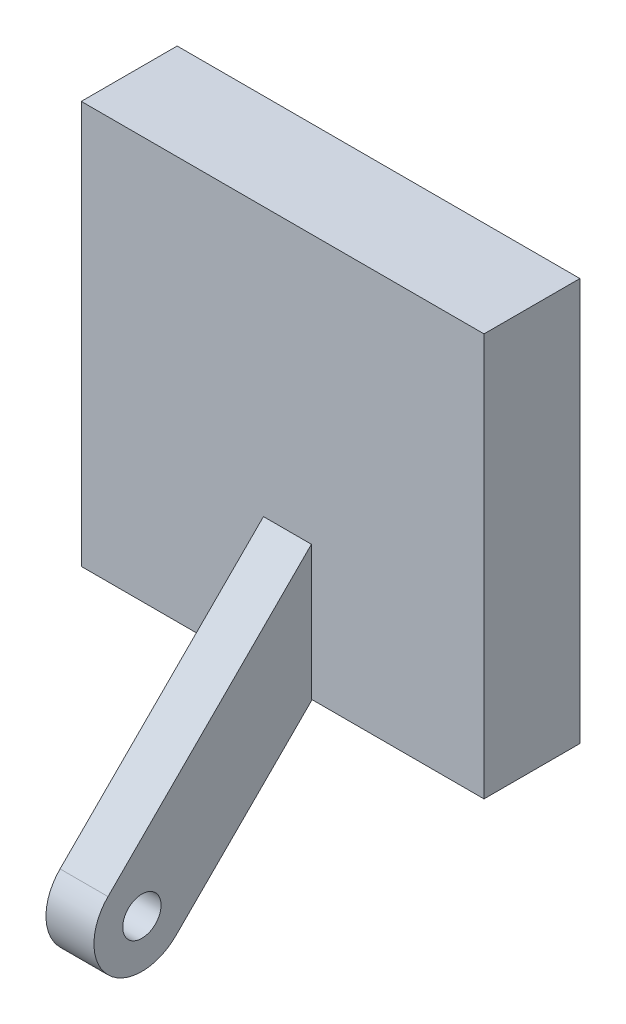
SolidWorks part; units mm, degrees
ref_plane "Alzado" through (0, 0, 0) normal (0, 0, 1) x (1, 0, 0)
ref_plane "Planta" through (0, 0, 0) normal (0, 1, 0) x (1, 0, 0)
ref_plane "Vista lateral" through (0, 0, 0) normal (1, 0, 0) x (0, 0, -1)
sketch "Croquis1" plane through (0, 0, 0) normal (1, 0, 0) x (0, 0, -1)
  line L0 (0, 0) -> (21.2132, 21.2132) construction
  line L4 (21.2132, 21.2132) -> (14.1421, 28.2843) construction
  line L5 (14.1421, 28.2843) -> (-7.0711, 7.0711) construction
  line L6 (-7.0711, 7.0711) -> (0, 0) construction
  line L7 (0, 0) -> (21.2132, 21.2132)
  line L8 (21.2132, 21.2132) -> (14.1421, 28.2843)
  line L9 (14.1421, 28.2843) -> (-7.0711, 7.0711)
  arc A3 (-7.0711, 7.0711) -> (0, 0) centre (-3.5355, 3.5355) ccw
  circle A4 centre (-3.5355, 3.5355) radius 2
extrude "Saliente-Extruir9" add sketch "Croquis1" along normal blind 5
sketch "Croquis7" plane through (5, 0, 0) normal (1, 0, 0) x (0, 0, -1)
  line L0 (14.1421, 28.2843) -> (14.1421, 56.2843) construction
  line L1 (14.1421, 56.2843) -> (24.1421, 56.2843) construction
  line L2 (24.1421, 56.2843) -> (24.1421, 14.2843) construction
  line L3 (24.1421, 14.2843) -> (14.2843, 14.2843) construction
  line L4 (0, 0) -> (21.2132, 21.2132) construction
  line L5 (14.2843, 14.2843) -> (14.1421, 28.2843) construction
  line L7 (14.1421, 56.2843) -> (24.1421, 56.2843)
  line L8 (14.1421, 56.2843) -> (14.1421, 14.2843)
  line L9 (14.1421, 14.2843) -> (24.1421, 14.2843)
  line L10 (24.1421, 56.2843) -> (24.1421, 14.2843)
extrude "Saliente-Extruir10" add sketch "Croquis7" against normal blind 24 and the other way blind 18
